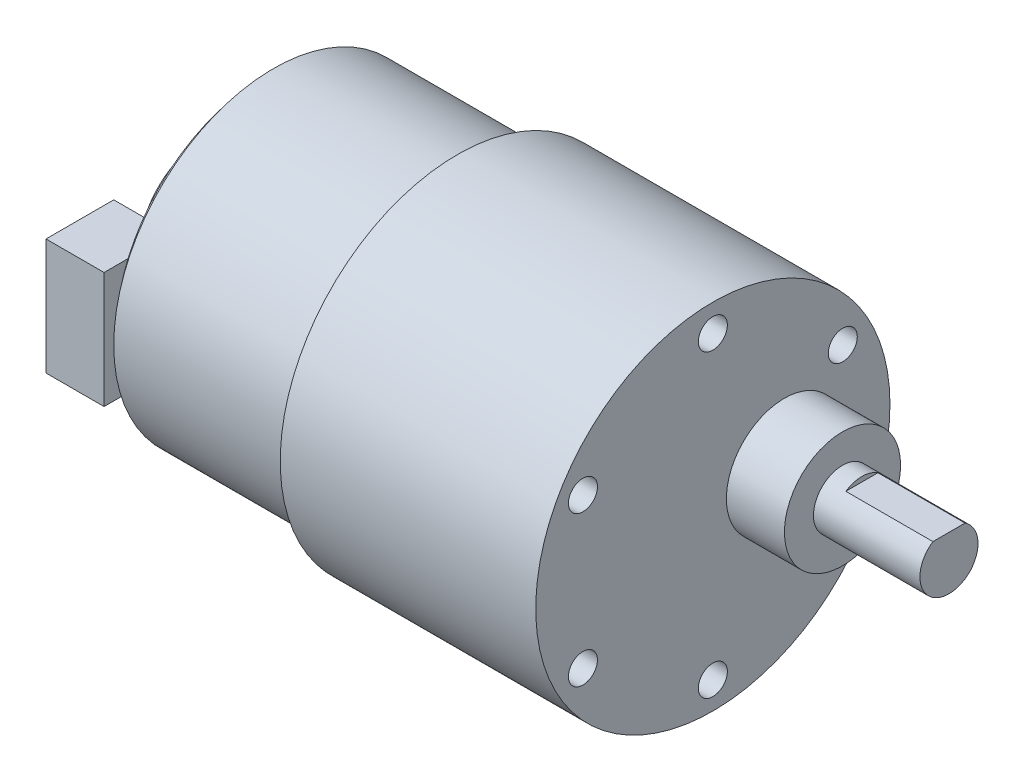
SolidWorks part; units mm, degrees
ref_plane "前视基准面" through (0, 0, 0) normal (0, 0, 1) x (1, 0, 0)
ref_plane "上视基准面" through (0, 0, 0) normal (0, 1, 0) x (1, 0, 0)
ref_plane "右视基准面" through (0, 0, 0) normal (1, 0, 0) x (0, 0, -1)
sketch "草图1" plane through (0, 0, 0) normal (1, 0, 0) x (0, 0, -1)
  circle A0 centre (0, 0) radius 18.3
extrude "凸台-拉伸1" add sketch "草图1" along normal blind 26.4
sketch "草图3" plane through (26.4, 0, 0) normal (1, 0, 0) x (0, 0, -1)
  circle A1 centre (7, 0) radius 6
  circle A3 centre (13.4234, 7.75) radius 1.5
  circle A4 centre (13.4234, -7.75) radius 1.5
  circle A5 centre (0, -15.5) radius 1.5
  circle A6 centre (-13.4234, -7.75) radius 1.5
  circle A7 centre (-13.4234, 7.75) radius 1.5
  circle A8 centre (0, 15.5) radius 1.5
  point P22 (0, 0)
  dimension "D1" = 6
sketch "草图4" plane through (0, 0, 0) normal (-1, 0, 0) x (0, 0, 1)
  circle A0 centre (0, 0) radius 16.5
extrude "凸台-拉伸2" add sketch "草图4" along normal blind 19
sketch "草图5" plane through (-19, 0, 0) normal (-1, 0, 0) x (0, 0, 1)
  circle A0 centre (0, 0) radius 15.25
extrude "凸台-拉伸3" add sketch "草图5" along normal blind 1
sketch "草图6" plane through (-20, 0, 0) normal (-1, 0, 0) x (0, 0, 1)
  circle A0 centre (0, 0) radius 6.9
extrude "凸台-拉伸4" add sketch "草图6" along normal blind 6
sketch "草图7" plane through (-20, 0, 0) normal (-1, 0, 0) x (0, 0, 1)
  line L2 (9.5, -6) -> (16.5, -6)
  line L3 (9.5, -6) -> (9.5, 6)
  line L4 (9.5, 6) -> (16.5, 6)
  line L5 (16.5, -6) -> (16.5, 6)
  line L6 (9.5, -6) -> (16.5, 6) construction
  line L7 (9.5, 6) -> (16.5, -6) construction
  point P3 (13, 0)
  dimension "D1" = 7
  dimension "D2" = 12
  dimension "D3" = 13
sketch "草图8" plane through (-26, 0, 0) normal (-1, 0, 0) x (0, 0, 1)
  line L0 (13, 0) -> (0, 0)
sketch "草图9" plane through (-20, 0, 0) normal (-1, 0, 0) x (0, 0, 1)
extrude "凸台-拉伸5" add sketch "草图7" along normal blind 6
sketch "草图13" plane through (26.4, 0, 0) normal (1, 0, 0) x (0, 0, -1)
sketch "草图16" plane through (26.4, 0, 0) normal (1, 0, 0) x (0, 0, -1)
extrude "切除-拉伸7" cut sketch "草图3" against normal blind 4 contours A7 | A6 | A5 | A4 | A3 | A8
sketch "草图18" plane through (26.4, 0, 0) normal (1, 0, 0) x (0, 0, -1)
  line L0 (0, 0) -> (1.3961, 0)
  circle A0 centre (7.3961, 0) radius 6
extrude "凸台-拉伸7" add sketch "草图18" along normal blind 6 contours A0
sketch "草图19" plane through (32.4, 0, 0) normal (1, 0, 0) x (0, 0, -1)
  circle A0 centre (7.3961, 0) radius 3
extrude "凸台-拉伸9" add sketch "草图19" along normal blind 2
sketch "草图23" plane through (34.4, 0, 0) normal (1, 0, 0) x (0, 0, -1)
  line L0 (7.3961, 2.5001) -> (7.3961, 3) construction
  line L3 (5.7379, 2.5001) -> (9.0544, 2.5001)
  circle A1 centre (7.3961, 0) radius 3
  arc A2 (5.7379, 2.5001) -> (9.0544, 2.5001) centre (7.3961, 0) ccw
  dimension "D1" = 0
extrude "凸台-拉伸10" add sketch "草图23" along normal blind 9
